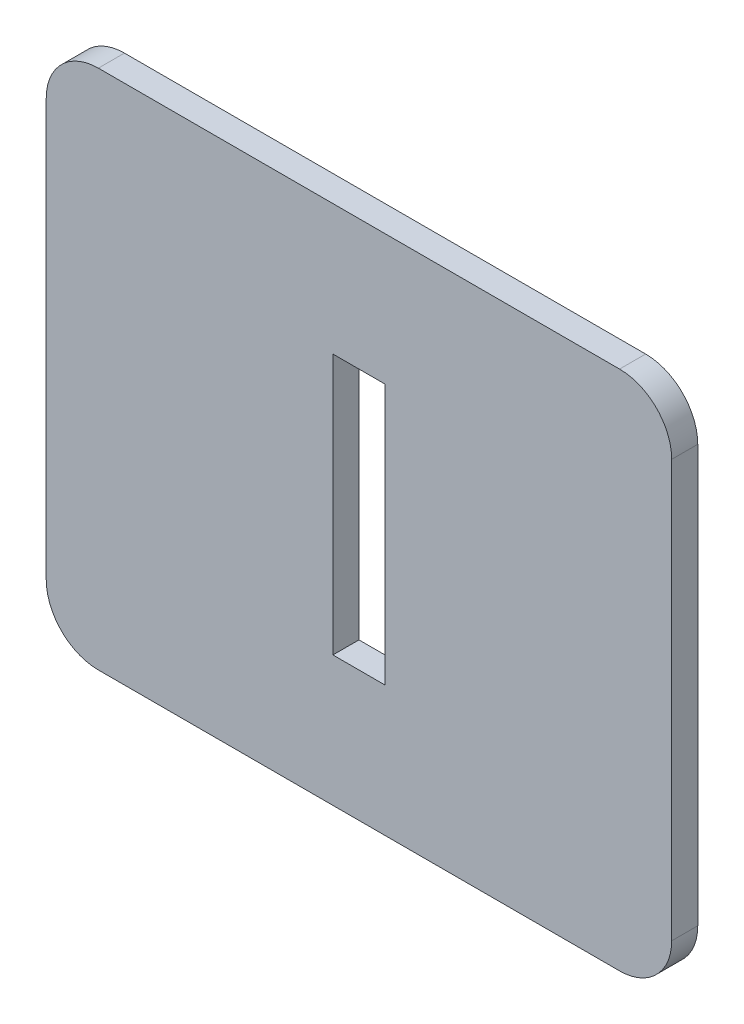
SolidWorks part; units mm, degrees
ref_plane "Front Plane" through (0, 0, 0) normal (0, 0, 1) x (1, 0, 0)
ref_plane "Top Plane" through (0, 0, 0) normal (0, 1, 0) x (1, 0, 0)
ref_plane "Right Plane" through (0, 0, 0) normal (1, 0, 0) x (0, 0, -1)
sketch "Sketch1" plane through (0, 0, 0) normal (0, 0, 1) x (1, 0, 0)
  line L0 (60, 100) -> (60, 0) construction
  line L1 (10, 0) -> (110, 0)
  line L2 (0, 10) -> (0, 90)
  line L3 (10, 100) -> (110, 100)
  line L4 (120, 10) -> (120, 90)
  line L6 (55, 75) -> (65, 75)
  line L7 (55, 75) -> (55, 25)
  line L8 (55, 25) -> (65, 25)
  line L9 (65, 75) -> (65, 25)
  line L10 (55, 75) -> (65, 25) construction
  line L11 (55, 25) -> (65, 75) construction
  arc A0 (110, 0) -> (120, 10) centre (110, 10) ccw
  arc A1 (10, 0) -> (0, 10) centre (10, 10) cw
  arc A2 (0, 90) -> (10, 100) centre (10, 90) cw
  arc A3 (110, 100) -> (120, 90) centre (110, 90) cw
  point P7 (60, 50)
  point P14 (120, 0)
  point P17 (0, 0)
  point P20 (0, 100)
  dimension "D5" = 10
  dimension "D1" = 100
  dimension "D2" = 120
  dimension "D3" = 10
  dimension "D4" = 50
extrude "Boss-Extrude1" add sketch "Sketch1" along normal blind 5
